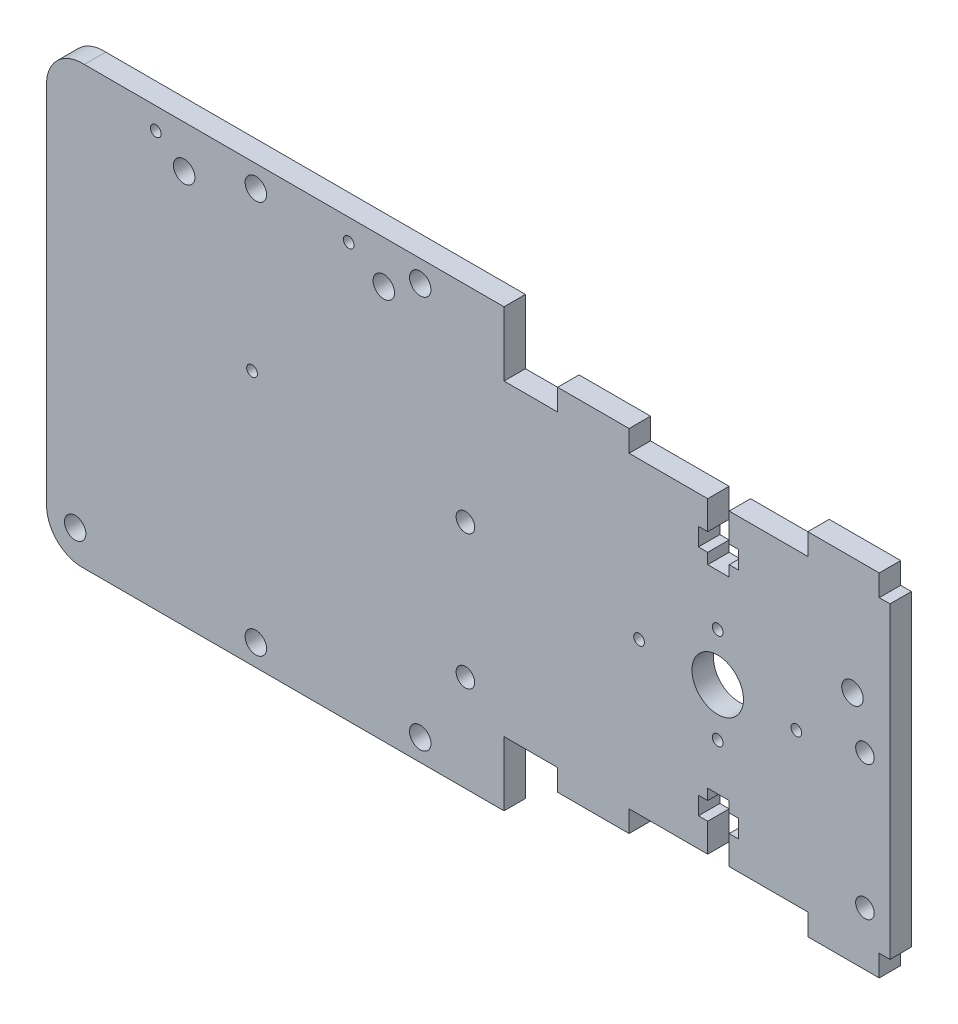
SolidWorks part; units mm, degrees
ref_plane "前基準面" through (0, 0, 0) normal (0, 0, 1) x (1, 0, 0)
ref_plane "上基準面" through (0, 0, 0) normal (0, 1, 0) x (1, 0, 0)
ref_plane "右基準面" through (0, 0, 0) normal (1, 0, 0) x (0, 0, -1)
sketch "草圖1" plane through (0, 0, 0) normal (0, 0, 1) x (1, 0, 0)
  line L0 (215.9988, 63.9869) -> (215.9988, 54.9869) construction
  line L1 (215.9988, 54.9869) -> (223.4988, 54.9869) construction
  line L2 (223.4988, 57.9869) -> (233.4988, 57.9869) construction
  line L3 (223.4988, 54.9869) -> (223.4988, 57.9869) construction
  line L4 (233.4988, 57.9869) -> (233.4988, 54.9869) construction
  line L5 (233.4988, 54.9869) -> (244.4988, 54.9869) construction
  line L6 (244.4988, 54.9869) -> (244.4988, 50.987) construction
  line L7 (244.4988, 50.987) -> (243.1988, 50.987) construction
  line L8 (243.1988, 50.987) -> (243.1988, 48.487) construction
  line L9 (243.1988, 48.487) -> (244.4988, 48.487) construction
  line L10 (244.4988, 48.487) -> (244.4988, 46.9869) construction
  line L11 (244.4988, 46.9869) -> (247.4988, 46.9869) construction
  line L12 (247.4988, 46.9869) -> (247.4988, 48.487) construction
  line L13 (247.4988, 48.487) -> (248.7988, 48.487) construction
  line L14 (248.7988, 48.487) -> (248.7988, 50.987) construction
  line L15 (248.7988, 50.987) -> (247.4988, 50.987) construction
  line L16 (247.4988, 50.987) -> (247.4988, 54.9869) construction
  line L17 (247.4988, 54.9869) -> (258.4988, 54.9869) construction
  line L18 (258.4988, 54.9869) -> (258.4988, 57.9869) construction
  line L19 (268.4988, 57.9869) -> (268.4988, 54.9869) construction
  line L20 (268.4988, 54.9869) -> (269.9988, 54.9869) construction
  line L21 (268.4988, 8.9069) -> (268.4988, 11.9069) construction
  line L22 (258.4988, 8.9069) -> (268.4988, 8.9069) construction
  line L23 (258.4988, 11.9069) -> (258.4988, 8.9069) construction
  line L24 (247.4988, 11.9069) -> (258.4988, 11.9069) construction
  line L25 (244.4988, 15.9069) -> (243.1988, 15.9069) construction
  line L26 (243.1988, 18.4069) -> (244.4988, 18.4069) construction
  line L27 (243.1988, 15.9069) -> (243.1988, 18.4069) construction
  line L28 (244.4988, 19.9069) -> (247.4988, 19.9069) construction
  line L29 (247.4988, 19.9069) -> (247.4988, 18.4069) construction
  line L30 (247.4988, 18.4069) -> (248.7988, 18.4069) construction
  line L31 (248.7988, 18.4069) -> (248.7988, 15.9069) construction
  line L32 (248.7988, 15.9069) -> (247.4988, 15.9069) construction
  line L33 (247.4988, 15.9069) -> (247.4988, 11.9069) construction
  line L34 (244.4988, 11.9069) -> (244.4988, 15.9069) construction
  line L35 (233.4988, 11.9069) -> (244.4988, 11.9069) construction
  line L36 (233.4988, 8.9069) -> (233.4988, 11.9069) construction
  line L37 (223.4988, 8.9069) -> (233.4988, 8.9069) construction
  line L38 (223.4988, 11.9069) -> (223.4988, 8.9069) construction
  line L39 (215.9988, 11.9069) -> (223.4988, 11.9069) construction
  line L40 (215.9988, 2.9069) -> (215.9988, 11.9069) construction
  line L41 (157.2788, 2.9069) -> (215.9988, 2.9069) construction
  line L42 (215.9988, 63.9869) -> (215.9988, 54.9869)
  line L43 (215.9988, 54.9869) -> (223.4988, 54.9869)
  line L44 (223.4988, 57.9869) -> (233.4988, 57.9869)
  line L45 (223.4988, 54.9869) -> (223.4988, 57.9869)
  line L46 (233.4988, 57.9869) -> (233.4988, 54.9869)
  line L47 (233.4988, 54.9869) -> (244.4988, 54.9869)
  line L48 (244.4988, 54.9869) -> (244.4988, 50.987)
  line L49 (244.4988, 50.987) -> (243.1988, 50.987)
  line L50 (243.1988, 50.987) -> (243.1988, 48.487)
  line L51 (243.1988, 48.487) -> (244.4988, 48.487)
  line L52 (244.4988, 48.487) -> (244.4988, 46.9869)
  line L53 (244.4988, 46.9869) -> (247.4988, 46.9869)
  line L54 (247.4988, 46.9869) -> (247.4988, 48.487)
  line L55 (247.4988, 48.487) -> (248.7988, 48.487)
  line L56 (248.7988, 48.487) -> (248.7988, 50.987)
  line L57 (248.7988, 50.987) -> (247.4988, 50.987)
  line L58 (247.4988, 50.987) -> (247.4988, 54.9869)
  line L59 (247.4988, 54.9869) -> (258.4988, 54.9869)
  line L60 (258.4988, 54.9869) -> (258.4988, 57.9869)
  line L61 (268.4988, 57.9869) -> (268.4988, 54.9869)
  line L62 (268.4988, 54.9869) -> (269.9988, 54.9869)
  line L63 (268.4988, 8.9069) -> (268.4988, 11.9069)
  line L64 (258.4988, 8.9069) -> (268.4988, 8.9069)
  line L65 (258.4988, 11.9069) -> (258.4988, 8.9069)
  line L66 (247.4988, 11.9069) -> (258.4988, 11.9069)
  line L67 (244.4988, 15.9069) -> (243.1988, 15.9069)
  line L68 (243.1988, 18.4069) -> (244.4988, 18.4069)
  line L69 (243.1988, 15.9069) -> (243.1988, 18.4069)
  line L70 (244.4988, 19.9069) -> (247.4988, 19.9069)
  line L71 (247.4988, 19.9069) -> (247.4988, 18.4069)
  line L72 (247.4988, 18.4069) -> (248.7988, 18.4069)
  line L73 (248.7988, 18.4069) -> (248.7988, 15.9069)
  line L74 (248.7988, 15.9069) -> (247.4988, 15.9069)
  line L75 (247.4988, 15.9069) -> (247.4988, 11.9069)
  line L76 (244.4988, 11.9069) -> (244.4988, 15.9069)
  line L77 (233.4988, 11.9069) -> (244.4988, 11.9069)
  line L78 (233.4988, 8.9069) -> (233.4988, 11.9069)
  line L79 (223.4988, 8.9069) -> (233.4988, 8.9069)
  line L80 (223.4988, 11.9069) -> (223.4988, 8.9069)
  line L81 (215.9988, 11.9069) -> (223.4988, 11.9069)
  line L82 (215.9988, 2.9069) -> (215.9988, 11.9069)
  line L83 (157.2788, 2.9069) -> (215.9988, 2.9069)
  line L84 (269.9988, 54.9869) -> (269.9988, 11.9069)
  line L85 (269.9988, 11.9069) -> (268.4988, 11.9069)
  line L86 (258.4988, 57.9869) -> (268.4988, 57.9869)
  line L87 (157.2788, 63.9869) -> (215.9988, 63.9869)
  line L88 (152.0002, 59.282) -> (152.0002, 7.8992)
  line L89 (244.4988, 19.9069) -> (244.4988, 18.4069)
  circle A0 centre (266.4988, 16.4069) radius 1.3 construction
  circle A1 centre (264.7488, 41.6069) radius 1.5 construction
  circle A2 centre (266.4988, 35.2069) radius 1.3 construction
  circle A3 centre (256.8988, 33.137) radius 0.75 construction
  circle A4 centre (245.8988, 39.8369) radius 0.75 construction
  circle A5 centre (245.8988, 26.4369) radius 0.75 construction
  circle A6 centre (234.8987, 33.1266) radius 0.75 construction
  arc A8 (152.0002, 7.8992) -> (157.2788, 2.9069) centre (157.0002, 7.8992) ccw construction
  circle A9 centre (155.9974, 7.2169) radius 1.5 construction
  circle A10 centre (181.2774, 5.9469) radius 1.5 construction
  circle A11 centre (204.2774, 5.9469) radius 1.5 construction
  circle A12 centre (210.5988, 16.4069) radius 1.3 construction
  circle A13 centre (210.5988, 35.2069) radius 1.3 construction
  circle A14 centre (180.7443, 38.5969) radius 0.75 construction
  circle A15 centre (204.2774, 60.9469) radius 1.5 construction
  circle A16 centre (199.1774, 58.0169) radius 1.5 construction
  circle A17 centre (194.2774, 60.9469) radius 0.75 construction
  circle A18 centre (181.2774, 60.9469) radius 1.5 construction
  circle A19 centre (167.2774, 60.9469) radius 0.75 construction
  circle A20 centre (171.2474, 58.0169) radius 1.5 construction
  arc A21 (157.2788, 63.9869) -> (152.0002, 59.282) centre (156.992, 58.9952) ccw construction
  circle A22 centre (266.4988, 16.4069) radius 1.3
  circle A23 centre (264.7488, 41.6069) radius 1.5
  circle A24 centre (266.4988, 35.2069) radius 1.3
  circle A25 centre (256.8988, 33.137) radius 0.75
  circle A26 centre (245.8988, 39.8369) radius 0.75
  circle A27 centre (245.8988, 26.4369) radius 0.75
  circle A28 centre (234.8987, 33.1266) radius 0.75
  arc A30 (152.0002, 7.8992) -> (157.2788, 2.9069) centre (157.0002, 7.8992) ccw
  circle A31 centre (155.9974, 7.2169) radius 1.5
  circle A32 centre (181.2774, 5.9469) radius 1.5
  circle A33 centre (204.2774, 5.9469) radius 1.5
  circle A34 centre (210.5988, 16.4069) radius 1.3
  circle A35 centre (210.5988, 35.2069) radius 1.3
  circle A36 centre (180.7443, 38.5969) radius 0.75
  circle A37 centre (204.2774, 60.9469) radius 1.5
  circle A38 centre (199.1774, 58.0169) radius 1.5
  circle A39 centre (194.2774, 60.9469) radius 0.75
  circle A40 centre (181.2774, 60.9469) radius 1.5
  circle A41 centre (167.2774, 60.9469) radius 0.75
  circle A42 centre (171.2474, 58.0169) radius 1.5
  arc A43 (157.2788, 63.9869) -> (152.0002, 59.282) centre (156.992, 58.9952) ccw
  circle A44 centre (245.8988, 33.137) radius 3.6
  point P0 (244.4988, 15.9069)
extrude "填料-伸長1" add sketch "草圖1" along normal blind 3
